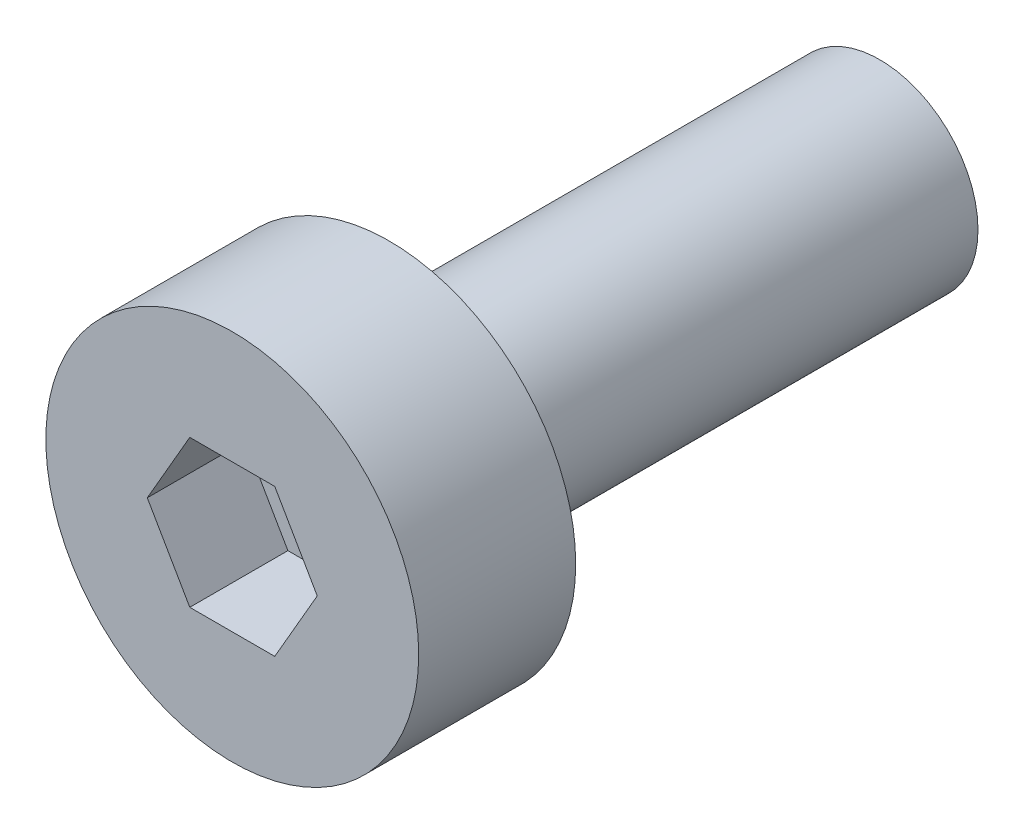
SolidWorks part; units mm, degrees
ref_plane "Plan de face" through (0, 0, 0) normal (0, 0, 1) x (1, 0, 0)
ref_plane "Plan de dessus" through (0, 0, 0) normal (0, 1, 0) x (1, 0, 0)
ref_plane "Plan de droite" through (0, 0, 0) normal (1, 0, 0) x (0, 0, -1)
sketch "Esquisse1" plane through (0, 0, 0) normal (0, 0, 1) x (1, 0, 0)
  circle A0 centre (0, 0) radius 1
  dimension "D1" = 2
extrude "Boss.-Extru.1" add sketch "Esquisse1" along normal blind 5
sketch "Esquisse2" plane through (0, 0, 5) normal (0, 0, 1) x (1, 0, 0)
  circle A0 centre (0, 0) radius 1.9
  dimension "D1" = 3.8
extrude "Boss.-Extru.2" add sketch "Esquisse2" along normal blind 1.6
sketch "Esquisse3" plane through (0, 0, 6.6) normal (0, 0, 1) x (1, 0, 0)
  line L1 (0.866, 0) -> (0.433, 0.75)
  line L2 (0.433, 0.75) -> (-0.433, 0.75)
  line L3 (-0.433, 0.75) -> (-0.866, 0)
  line L4 (-0.866, 0) -> (-0.433, -0.75)
  line L5 (-0.433, -0.75) -> (0.433, -0.75)
  line L6 (0.433, -0.75) -> (0.866, 0)
  circle A0 centre (0, 0) radius 0.75 construction
  dimension "D1" = 1.5
extrude "Enlèv. mat.-Extru.1" cut sketch "Esquisse3" against normal blind 1
